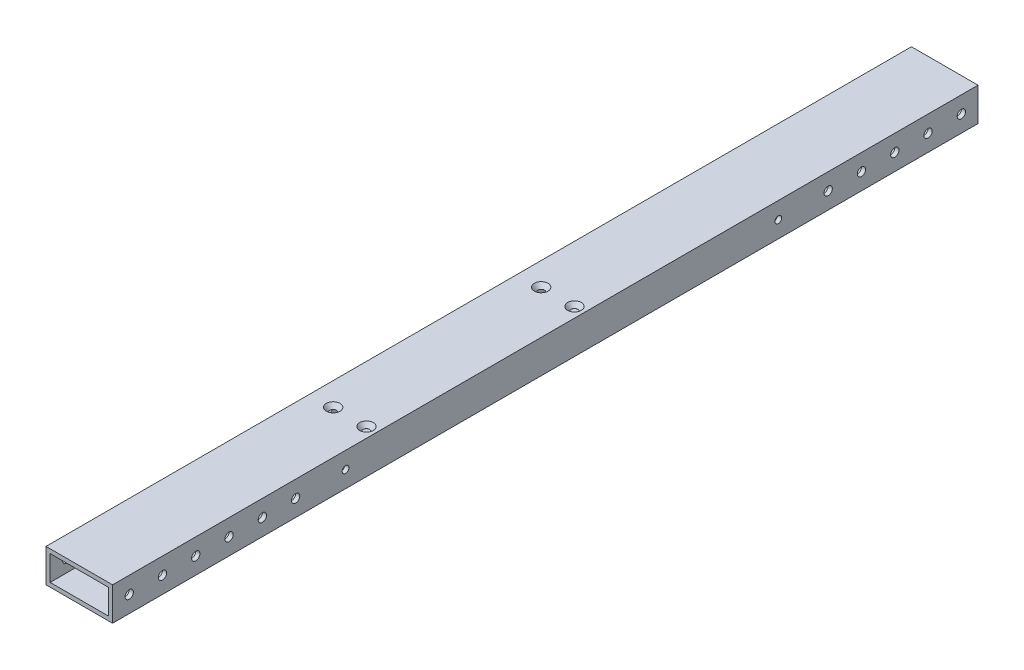
SolidWorks part; units mm, degrees
material "6061 Alloy"
ref_plane "Front Plane" through (0, 0, 0) normal (0, 0, 1) x (1, 0, 0)
ref_plane "Top Plane" through (0, 0, 0) normal (0, 1, 0) x (1, 0, 0)
ref_plane "Right Plane" through (0, 0, 0) normal (1, 0, 0) x (0, 0, -1)
sketch "Sketch1" plane through (0, 0, 0) normal (0, 0, 1) x (1, 0, 0)
  line L0 (-22.225, 9.525) -> (22.225, 9.525)
  line L2 (-25.4, 12.7) -> (25.4, 12.7)
  line L3 (-25.4, 12.7) -> (-25.4, -12.7)
  line L4 (-25.4, -12.7) -> (25.4, -12.7)
  line L5 (25.4, 12.7) -> (25.4, -12.7)
  line L10 (22.225, 9.525) -> (22.225, -9.525)
  line L11 (-22.225, -9.525) -> (22.225, -9.525)
  line L12 (-22.225, 9.525) -> (-22.225, -9.525)
  point P12 (0, 12.7)
  point P14 (25.4, 0)
  dimension "Wall Thickness" = 3.175
  dimension "Outside Width" = 50.8
  dimension "Outside Height" = 25.4
  dimension "Inside Height" = 19.05
  dimension "Inside Width" = 44.45
sketch "Sketch2" plane through (0, 0, 0) normal (1, 0, 0) x (0, 0, -1)
  line L0 (330.2, 0) -> (-330.2, 0)
  point P4 (0, 0)
  point P7 (-330.2, 0)
  point P10 (330.2, 0)
  dimension "Length" = 660.4
sketch "Sketch3" plane through (0, 0, 0) normal (0, 0, 1) x (1, 0, 0)
  line L21 (25.4, 12.7) -> (-25.4, 12.7)
  line L22 (25.4, -12.7) -> (25.4, 12.7)
  line L23 (-25.4, -12.7) -> (25.4, -12.7)
  line L24 (-25.4, 12.7) -> (-25.4, -12.7)
  line L25 (25.4, 12.7) -> (-25.4, 12.7)
  line L26 (25.4, -12.7) -> (25.4, 12.7)
  line L27 (-25.4, -12.7) -> (25.4, -12.7)
  line L28 (-25.4, 12.7) -> (-25.4, -12.7)
  line L29 (22.225, 9.525) -> (-22.225, 9.525)
  line L30 (22.225, -9.525) -> (22.225, 9.525)
  line L31 (-22.225, -9.525) -> (22.225, -9.525)
  line L32 (-22.225, 9.525) -> (-22.225, -9.525)
  line L33 (22.225, 9.525) -> (-22.225, 9.525)
  line L34 (22.225, -9.525) -> (22.225, 9.525)
  line L35 (-22.225, -9.525) -> (22.225, -9.525)
  line L36 (-22.225, 9.525) -> (-22.225, -9.525)
  dimension "D1" = 0
  dimension "D2" = 0
extrude "Boss-Extrude1" add sketch "Sketch3" along normal up to vertex (330.2 mm away) and the other way up to vertex (330.2 mm away) up to point (0, 0, 330.2) other way up to point (0, 0, -330.2)
sketch "Drawing Reference" plane through (0, 0, 0) normal (1, 0, 0) x (0, 0, -1)
  line L0 (-330.2, 0) -> (330.2, 0) construction
  line L1 (0, -12.7) -> (0, 12.7) construction
  line L2 (-330.2, -12.7) -> (330.2, -12.7) construction
  line L5 (-330.2, 12.7) -> (330.2, 12.7) construction
  point P7 (-293.624, 0)
  point P8 (293.624, 0)
  dimension "D1" = 36.576
sketch "Sketch5" plane through (25.4, 0, 0) normal (1, 0, 0) x (0, 0, -1)
  line L2 (-266.7, 0) -> (-241.3, 0)
  line L3 (-241.3, 0) -> (-215.9, 0)
  line L4 (-215.9, 0) -> (-190.5, 0)
  line L5 (-317.5, 0) -> (-330.2, 0)
  line L6 (-330.2, -12.7) -> (-330.2, 12.7) construction
  line L7 (-317.5, 0) -> (-292.1, 0)
  line L8 (-292.1, 0) -> (-266.7, 0)
sketch "Sketch8" plane through (25.4, 0, 0) normal (1, 0, 0) x (0, 0, -1)
  line L0 (330.2, 0) -> (292.1, 0)
  line L1 (330.2, -12.7) -> (330.2, 12.7) construction
  line L2 (292.1, 0) -> (266.7, 0)
  line L3 (266.7, 0) -> (241.3, 0)
  line L4 (241.3, 0) -> (215.9, 0)
  line L5 (330.2, 0) -> (317.5, 0)
hole_wizard "1/4 (0.25) Diameter Hole3" positions "Sketch12" profile "Sketch13" hole size "1/4" standard "ANSI Inch" end condition through all
sketch "Sketch12" plane through (-25.4, 0, 0) normal (-1, 0, 0) x (0, 0, 1)
  point P4 (-317.5, 0)
sketch "Sketch13" plane through (-25.4, 0, -317.5) normal (0, 1, 0) x (0, 0, 1)
  line L0 (0, 0) -> (0, 50.8)
  line L1 (0, 50.8) -> (3.175, 50.8)
  line L2 (3.175, 50.8) -> (3.175, 0)
  line L5 (3.175, 0) -> (0, 0)
  line L11 (0, -6.35) -> (0, 107.95) construction
  dimension "Thru Hole Dia." = 6.35
  dimension "Thru Hole Depth" = 50.8
hole_wizard "1/4 (0.25) Diameter Hole4" positions "Sketch14" profile "Sketch15" hole size "1/4" standard "ANSI Inch" end condition through all
sketch "Sketch14" plane through (-25.4, 0, 0) normal (-1, 0, 0) x (0, 0, 1)
  point P0 (292.1, 0)
  point P3 (317.5, 0)
sketch "Sketch15" plane through (-25.4, 0, 292.1) normal (0, 1, 0) x (0, 0, 1)
  line L0 (0, 0) -> (0, 50.8)
  line L1 (0, 50.8) -> (3.175, 50.8)
  line L2 (3.175, 50.8) -> (3.175, 0)
  line L5 (3.175, 0) -> (0, 0)
  line L11 (0, -6.35) -> (0, 107.95) construction
  dimension "Thru Hole Dia." = 6.35
  dimension "Thru Hole Depth" = 50.8
hole_wizard "1/4 (0.25) Diameter Hole5" positions "Sketch17" profile "Sketch18" hole size "1/4" standard "ANSI Inch" end condition through all
sketch "Sketch17" plane through (25.4, 0, 0) normal (1, 0, 0) x (0, 0, -1)
  point P0 (292.1, 0)
  point P3 (266.7, 0)
sketch "Sketch18" plane through (25.4, 0, -292.1) normal (0, 1, 0) x (0, 0, -1)
  line L0 (0, 0) -> (0, 50.8)
  line L1 (0, 50.8) -> (3.175, 50.8)
  line L2 (3.175, 50.8) -> (3.175, 0)
  line L5 (3.175, 0) -> (0, 0)
  line L11 (0, -6.35) -> (0, 107.95) construction
  dimension "Thru Hole Dia." = 6.35
  dimension "Thru Hole Depth" = 50.8
hole_wizard "1/4 (0.25) Diameter Hole6" positions "Sketch19" profile "Sketch20" hole size "1/4" standard "ANSI Inch" end condition through all
sketch "Sketch19" plane through (25.4, 0, 0) normal (1, 0, 0) x (0, 0, -1)
  point P0 (215.9, 0)
  point P3 (241.3, 0)
sketch "Sketch20" plane through (25.4, 0, -215.9) normal (0, 1, 0) x (0, 0, -1)
  line L0 (0, 0) -> (0, 50.8)
  line L1 (0, 50.8) -> (3.175, 50.8)
  line L2 (3.175, 50.8) -> (3.175, 0)
  line L5 (3.175, 0) -> (0, 0)
  line L11 (0, -6.35) -> (0, 107.95) construction
  dimension "Thru Hole Dia." = 6.35
  dimension "Thru Hole Depth" = 50.8
hole_wizard "1/4 (0.25) Diameter Hole7" positions "Sketch21" profile "Sketch22" hole size "1/4" standard "ANSI Inch" end condition through all
sketch "Sketch21" plane through (25.4, 0, 0) normal (1, 0, 0) x (0, 0, -1)
  point P0 (-190.5, 0)
  point P3 (-215.9, 0)
sketch "Sketch22" plane through (25.4, 0, 190.5) normal (0, 1, 0) x (0, 0, -1)
  line L0 (0, 0) -> (0, 50.8)
  line L1 (0, 50.8) -> (3.175, 50.8)
  line L2 (3.175, 50.8) -> (3.175, 0)
  line L5 (3.175, 0) -> (0, 0)
  line L11 (0, -6.35) -> (0, 107.95) construction
  dimension "Thru Hole Dia." = 6.35
  dimension "Thru Hole Depth" = 50.8
hole_wizard "1/4 (0.25) Diameter Hole8" positions "Sketch23" profile "Sketch24" hole size "1/4" standard "ANSI Inch" end condition through all
sketch "Sketch23" plane through (25.4, 0, 0) normal (1, 0, 0) x (0, 0, -1)
  point P0 (-266.7, 0)
  point P3 (-241.3, 0)
sketch "Sketch24" plane through (25.4, 0, 266.7) normal (0, 1, 0) x (0, 0, -1)
  line L0 (0, 0) -> (0, 50.8)
  line L1 (0, 50.8) -> (3.175, 50.8)
  line L2 (3.175, 50.8) -> (3.175, 0)
  line L5 (3.175, 0) -> (0, 0)
  line L11 (0, -6.35) -> (0, 107.95) construction
  dimension "Thru Hole Dia." = 6.35
  dimension "Thru Hole Depth" = 50.8
sketch "Sketch25" plane through (25.4, 0, 0) normal (1, 0, 0) x (0, 0, -1)
  line L0 (-190.5, 0) -> (-152.4, 0)
  line L1 (215.9, 0) -> (177.8, 0)
hole_wizard "13/64 (0.20313) Diameter Hole1" positions "Sketch26" profile "Sketch27" hole size "13/64" standard "ANSI Inch" end condition through all
sketch "Sketch26" plane through (25.4, 0, 0) normal (1, 0, 0) x (0, 0, -1)
  point P0 (-152.4, 0)
  point P3 (177.8, 0)
sketch "Sketch27" plane through (25.4, 0, 152.4) normal (0, 1, 0) x (0, 0, -1)
  line L0 (0, 0) -> (0, 50.8)
  line L1 (0, 50.8) -> (2.5798, 50.8)
  line L2 (2.5798, 50.8) -> (2.5798, 0)
  line L5 (2.5798, 0) -> (0, 0)
  line L11 (0, -6.35) -> (0, 107.95) construction
  dimension "Thru Hole Dia." = 5.1595
  dimension "Thru Hole Depth" = 50.8
hole_wizard "1/2 (0.5) Diameter Hole1" positions "Sketch33" profile "Sketch34" hole size "1/2" standard "ANSI Inch"
sketch "Sketch33" plane through (-25.4, 0, 0) normal (-1, 0, 0) x (0, 0, 1)
  point P0 (-146.05, 0)
  point P3 (120.65, 0)
sketch "Sketch34" plane through (-25.4, 0, -146.05) normal (0, 1, 0) x (0, 0, 1)
  line L0 (0, 0) -> (0, 10.1655)
  line L1 (0, 10.1655) -> (6.35, 6.35)
  line L2 (6.35, 6.35) -> (6.35, 0)
  line L5 (6.35, 0) -> (0, 0)
  line L10 (0, 10.1655) -> (-6.35, 6.35) construction
  line L11 (0, -6.35) -> (0, 107.95) construction
  dimension "Hole Dia." = 12.7
  dimension "Hole Depth" = 6.35
  dimension "Drill Angle" = 118
sketch "Sketch37" plane through (0, -12.7, 0) normal (0, -1, 0) x (-1, 0, 0)
  line L0 (-25.4, -330.2) -> (-25.4, -128.7188) construction
  line L1 (-25.4, -330.2) -> (-25.4, 330.2) construction
  line L2 (-25.4, -128.7188) -> (-17.6522, -128.7188) construction
  line L3 (-17.6522, -128.7188) -> (7.7478, -128.7188) construction
  line L4 (-25.4, -128.7188) -> (-25.4, 30.0312) construction
  line L5 (-25.4, 30.0312) -> (-17.6522, 30.0312) construction
  line L6 (-17.6522, 30.0312) -> (7.7478, 30.0312) construction
  dimension "D1" = 201.4812
  dimension "D2" = 7.7478
  dimension "D3" = 25.4
  dimension "D4" = 7.7478
  dimension "D5" = 25.4
hole_wizard "#10 Clearance Hole1" positions "Sketch38" profile "Sketch39" hole size "#10" standard "ANSI Inch" end condition through all
sketch "Sketch38" plane through (0, -12.7, 0) normal (0, -1, 0) x (-1, 0, 0)
  point P0 (7.7478, 30.0312)
  point P3 (-17.6522, 30.0312)
  point P6 (-17.6522, -128.7188)
  point P9 (7.7478, -128.7188)
sketch "Sketch39" plane through (-7.7478, -12.7, -30.0312) normal (1, 0, 0) x (0, 0, -1)
  line L0 (0, 0) -> (0, 25.4)
  line L1 (0, 25.4) -> (5.2197, 25.4)
  line L2 (2.4892, 22.2589) -> (2.4892, 0)
  line L5 (2.4892, 0) -> (0, 0)
  line L7 (5.2197, 25.4) -> (2.4892, 22.2589)
  line L8 (-5.2197, 25.4) -> (-2.4892, 22.2589) construction
  line L11 (0, -6.35) -> (0, 107.95) construction
  dimension "Thru Hole Dia." = 4.9784
  dimension "Thru Hole Depth" = 25.4
  dimension "Far C'Sink Dia." = 10.4394
  dimension "Far C'Sink Angle" = 82
equation "\"D1@Drawing Reference\"=\"Outside Width@Sketch1\" * 0.72"
